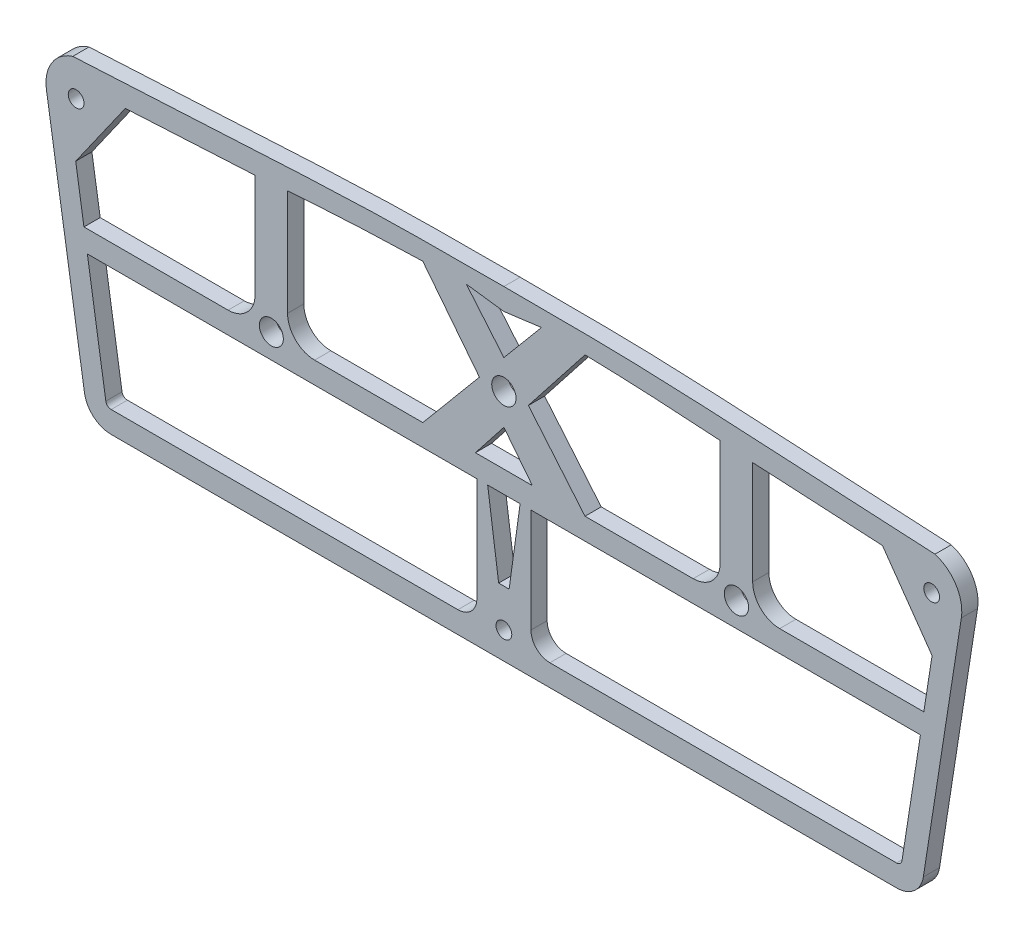
SolidWorks part; units mm, degrees
ref_plane "Alzado" through (0, 0, 0) normal (0, 0, 1) x (1, 0, 0)
ref_plane "Planta" through (0, 0, 0) normal (0, 1, 0) x (1, 0, 0)
ref_plane "Vista lateral" through (0, 0, 0) normal (1, 0, 0) x (0, 0, -1)
sketch "Croquis1" plane through (0, 0, 0) normal (0, 0, 1) x (1, 0, 0)
  line L0 (72.621, -42.7139) -> (-72.621, -42.7139)
  line L1 (79.7182, 14.2861) -> (-79.7182, 14.2861) construction
  line L2 (0, 14.2861) -> (0, 17.2861) construction
  line L3 (-77.7935, 17.2861) -> (77.7935, 17.2861) construction
  line L4 (0, -40.4126) -> (0, 34.1548) construction
  line L5 (-25, 41.2162) -> (-25, -46.3712) construction
  line L6 (-77.5611, -38.4855) -> (-84.5891, 6.5113)
  line L11 (25, 41.2162) -> (25, -46.3712) construction
  line L14 (77.5611, -38.4855) -> (84.5891, 6.5113)
  arc A0 (84.5891, 6.5113) -> (79.7182, 14.2861) centre (77.6729, 7.5915) ccw
  arc A1 (77.5611, -38.4855) -> (72.621, -42.7139) centre (72.621, -37.7139) cw
  arc A2 (-77.5611, -38.4855) -> (-72.621, -42.7139) centre (-72.621, -37.7139) ccw
  arc A3 (-84.5891, 6.5113) -> (-79.7182, 14.2861) centre (-77.6729, 7.5915) cw
  conic Q0 (79.7182, 14.2861) -> (0, 17.2861) control (25, 17.2861) rho 0.75
  conic Q1 (-79.7182, 14.2861) -> (0, 17.2861) control (-25, 17.2861) rho 0.75
  point P15 (-84.627, 12.5288)
  point P27 (0, -42.7139)
  point P28 (0, -42.7139)
  point P40 (0, 9.5288)
  point P61 (0, -42.7139)
  point P62 (84.627, 12.5288)
  dimension "D1" = 5
  dimension "D2" = 7
  dimension "D4" = 60
  dimension "D3" = 3
extrude "Saliente-Extruir3" add sketch "Croquis1" along normal blind 3 contours Q0 Q1 A3 L6 A2 L0 A1 L14 A0
sketch "Croquis10" plane through (0, 0, 0) normal (0, 0, -1) x (-1, 0, 0)
  line L0 (-79.1761, -2.225) -> (-70, 10.8116)
  line L1 (79.1761, -2.225) -> (70, 10.8116)
  line L2 (46, -6.9974) -> (46, 12.0975)
  line L3 (-89.1533, -2.1273) -> (0, -3.0001) construction
  line L4 (-70, 32.4884) -> (-70, -57.6963) construction
  line L5 (70, -55.635) -> (70, -62.635) construction
  line L6 (-80.637, 7.1286) -> (-73.609, -37.8682)
  line L7 (-72.621, -38.7139) -> (72.621, -38.7139)
  line L8 (73.609, -37.8682) -> (80.637, 7.1286)
  line L9 (-79.1761, -2.225) -> (-77.6497, -11.9974)
  line L10 (-72.621, -38.7139) -> (-8.5, -38.7139)
  line L11 (73.609, -37.8682) -> (77.025, -15.9974)
  line L12 (0, -66.0706) -> (0, -38.7139) construction
  line L13 (-5, -34.7139) -> (-5, -35.2139)
  line L14 (5, -34.7139) -> (5, -35.2139)
  line L15 (-72.621, -42.7139) -> (72.621, -42.7139) construction
  line L16 (8.5, -38.7139) -> (72.621, -38.7139)
  line L17 (0, -30.688) -> (0, -3.0001) construction
  line L18 (2.4598, -37.7139) -> (-1.8908, -37.7139) construction
  line L19 (77.5724, -13.7139) -> (-84.3115, -13.7139) construction
  line L20 (77.025, -15.9974) -> (15, -15.9974)
  line L21 (35, -11.9974) -> (15, -11.9974)
  line L22 (15, 26.347) -> (15, -53.1774) construction
  line L24 (-15, -38.7139) -> (-15, -55.635) construction
  line L26 (-0.9683, -30.688) -> (-3, -15.9974)
  line L27 (0.9683, -30.688) -> (3, -15.9974)
  line L28 (-0.9683, -30.688) -> (0, -30.688)
  line L29 (3, -15.9974) -> (0, -15.9974)
  line L30 (-15, -15.9974) -> (-77.025, -15.9974)
  line L31 (79.1761, -2.225) -> (77.6497, -11.9974)
  line L32 (-77.025, -15.9974) -> (-73.609, -37.8682)
  line L33 (40, -6.9974) -> (40, 12.6316)
  line L34 (5.2644, -11.9561) -> (-5.2644, -11.9561)
  line L35 (-46, 12.0975) -> (-46, -6.9974)
  line L36 (51, -11.9974) -> (77.6497, -11.9974)
  line L37 (-51, -11.9974) -> (-77.6497, -11.9974)
  line L38 (-40, 12.6316) -> (-40, -6.9974)
  line L39 (-15, -11.9974) -> (-4.5237, 0.5057)
  line L40 (15, -11.9974) -> (4.5237, 0.5057)
  line L42 (-15, -11.9974) -> (-35, -11.9974)
  line L44 (46, -6.9974) -> (40, -6.9974) construction
  line L45 (43, -6.9974) -> (43, -15.9974) construction
  line L46 (-40, -3.91) -> (-46, -3.91) construction
  line L47 (-46, -3.91) -> (-43, -3.91) construction
  line L48 (-43, -3.91) -> (-43, -19.0848) construction
  line L49 (0, -30.688) -> (0.9683, -30.688)
  line L50 (0, -15.9974) -> (-3, -15.9974)
  line L51 (-5.2644, -11.9561) -> (0, -5.2536)
  line L52 (-15, 13.8437) -> (-4.5237, 0.5057)
  line L53 (0, 5.9046) -> (-6.9466, 14.1951)
  line L54 (0, 5.9046) -> (6.9466, 14.1951)
  line L55 (0, 5.9046) -> (0, 45.5866) construction
  line L56 (1.7565, -3.0173) -> (92.9339, -3.91) construction
  line L57 (4.5237, 0.5057) -> (15, 13.8437)
  line L58 (0, -5.2536) -> (5.2644, -11.9561)
  line L59 (4.5237, 0.5057) -> (-4.5237, 0.5057) construction
  line L60 (43, -11.4974) -> (-56.9157, -11.4974) construction
  line L61 (15, -15.9974) -> (5, -15.9974)
  line L62 (5, -15.9974) -> (5, -34.7139)
  line L63 (-5, -34.7139) -> (-5, -15.9974)
  line L64 (-5, -15.9974) -> (-15, -15.9974)
  arc A0 (-5, -35.2139) -> (-8.5, -38.7139) centre (-8.5, -35.2139) cw
  arc A1 (8.5, -38.7139) -> (5, -35.2139) centre (8.5, -35.2139) cw
  arc A2 (40, -6.9974) -> (35, -11.9974) centre (35, -6.9974) cw
  arc A3 (46, -6.9974) -> (51, -11.9974) centre (51, -6.9974) ccw
  arc A4 (-51, -11.9974) -> (-46, -6.9974) centre (-51, -6.9974) ccw
  arc A5 (-35, -11.9974) -> (-40, -6.9974) centre (-35, -6.9974) cw
  circle A6 centre (43, -11.4974) radius 2.2165
  circle A7 centre (-43, -11.4974) radius 2.25
  arc A8 (-78.9106, 10.3243) -> (-80.637, 7.1286) centre (-77.6729, 7.5915) ccw
  arc A9 (-73.609, -37.8682) -> (-72.621, -38.7139) centre (-72.621, -37.7139) ccw
  arc A10 (72.621, -38.7139) -> (73.609, -37.8682) centre (72.621, -37.7139) ccw
  arc A11 (80.637, 7.1286) -> (78.9106, 10.3243) centre (77.6729, 7.5915) ccw
  circle A12 centre (0, 0.5057) radius 2.25
  arc A13 (-73.609, -37.8682) -> (-72.621, -38.7139) centre (-72.621, -37.7139) ccw
  arc A14 (72.621, -38.7139) -> (73.609, -37.8682) centre (72.621, -37.7139) ccw
  spline S0 degree 3 poles (-46, 12.0975) (-50.3985, 11.8702) (-54.7965, 11.6342) (-62.7964, 11.2034) (-66.3982, 11.008) (-70, 10.8116) knots 0.582707 0.582707 0.582707 0.582707 0.75 0.75 0.887012 0.887012 0.887012 0.887012
  spline S1 degree 3 poles (40, 12.6316) (39.8254, 12.6429) (39.6508, 12.6542) (36.1907, 12.8778) (32.9047, 13.0827) (26.3302, 13.4427) (23.0414, 13.5928) (18.1671, 13.7577) (16.5836, 13.8034) (15, 13.8437) knots 0.493358 0.493358 0.493358 0.493358 0.5 0.5 0.625 0.625 0.75 0.75 0.810141 0.810141 0.810141 0.810141
  spline S2 degree 3 poles (6.9466, 14.1951) (4.6306, 13.8958) (2.3152, 13.5918) (0, 13.2861) knots 0.911343 0.911343 0.911343 0.911343 1 1 1 1
  spline S3 degree 3 poles (-15, 13.8437) (-16.5836, 13.8034) (-18.1671, 13.7577) (-23.0414, 13.5928) (-26.3302, 13.4427) (-32.9047, 13.0827) (-36.1907, 12.8778) (-39.6508, 12.6542) (-39.8254, 12.6429) (-40, 12.6316) knots 0.189858 0.189858 0.189858 0.189858 0.25 0.25 0.375 0.375 0.5 0.5 0.506642 0.506642 0.506642 0.506642
  spline S4 degree 3 poles (1023.8412, 337.5933) (688.2712, -34.0559) (374.0407, -5.5562) (52.6222, 11.7513) (46.0499, 12.1034) (36.1891, 12.5892) (32.9019, 12.7438) (26.3256, 13.0031) (23.0364, 13.1028) (16.455, 13.2247) (13.1641, 13.2517) (-151.4659, 14.0208) (-312.9806, -13.553) (-468.678, 896.6381) knots -11.726351 -11.726351 -11.726351 -11.726351 0.25 0.25 0.5 0.5 0.625 0.625 0.75 0.75 0.875 0.875 7.003082 7.003082 7.003082 7.003082 only from (78.9106, 10.3243) to (0, 13.2861)
  spline S5 degree 3 poles (468.6965, 896.6433) (312.9806, -13.5531) (151.4662, 14.0208) (-13.1641, 13.2517) (-16.455, 13.2247) (-23.0364, 13.1028) (-26.3256, 13.0031) (-32.9019, 12.7438) (-36.1891, 12.5892) (-46.0499, 12.1034) (-52.6222, 11.7513) (-374.041, -5.5562) (-688.2719, -34.056) (-1023.8404, 337.5944) knots -6.00309 -6.00309 -6.00309 -6.00309 0.125 0.125 0.25 0.25 0.375 0.375 0.5 0.5 0.75 0.75 12.726363 12.726363 12.726363 12.726363 only from (0, 13.2861) to (-78.9106, 10.3243)
  spline S6 degree 3 poles (70, 10.8116) (66.3982, 11.008) (62.7964, 11.2034) (54.7965, 11.6342) (50.3985, 11.8702) (46, 12.0975) knots 0.112988 0.112988 0.112988 0.112988 0.25 0.25 0.417293 0.417293 0.417293 0.417293
  spline S7 degree 3 poles (0, 13.2861) (-2.3152, 13.5918) (-4.6306, 13.8958) (-6.9466, 14.1951) knots 0 0 0 0 0.088657 0.088657 0.088657 0.088657
  point P8 (-79.1761, -2.225)
  point P9 (-70, 10.8116)
  point P43 (0, -37.7139)
  point P54 (-15, -15.9974)
  point P55 (15, -15.9974)
  point P74 (46, -11.9974)
  dimension "D17" = 5
  dimension "D18" = 5
  dimension "D21" = 3
  dimension "D2" = 70
  dimension "D3" = 70
  dimension "D4" = 3
  dimension "D5" = 10
  dimension "D9" = 5
  dimension "D10" = 25
  dimension "D11" = 4
  dimension "D13" = 15
  dimension "D14" = 40
  dimension "D15" = 6
  dimension "D22" = 3
  dimension "D1" = 4
extrude "Cortar-Extruir2" cut sketch "Croquis10" against normal blind 3
sketch "Croquis11" plane through (0, 0, 0) normal (0, 0, -1) x (-1, 0, 0)
  line L0 (-74.588, 4.2933) -> (-83.6049, 11.3079) construction
  line L1 (-70, 10.8116) -> (-79.1761, -2.225) construction
  line L2 (74.588, 4.2933) -> (83.6049, 11.3079) construction
  line L3 (79.1761, -2.225) -> (70, 10.8116) construction
  line L4 (0, 0) -> (0, -72.0529) construction
  line L5 (4.267, -37.7139) -> (-4.5681, -37.7139) construction
  line L6 (-72.621, -42.7139) -> (72.621, -42.7139) construction
  arc A0 (-79.7182, 14.2861) -> (-84.5891, 6.5113) centre (-77.6729, 7.5915) ccw construction
  arc A1 (84.5891, 6.5113) -> (79.7182, 14.2861) centre (77.6729, 7.5915) ccw construction
  point P14 (79.0965, 7.8006)
  point P15 (-79.0965, 7.8006)
  point P23 (0, -37.7139)
  dimension "D1" = 5
hole_wizard "Taladro de margen para #32" positions "Croquis3D1" profile "Croquis12" hole size "#3" standard "Ansi Inch" end condition through all
sketch3d "Croquis3D1"
  point P0 (79.0965, 7.8006, 0)
  point P3 (-79.0965, 7.8006, 0)
sketch "Croquis12" plane through (79.0965, 7.8006, 0) normal (1, 0, 0) x (0, 1, 0)
  line L0 (0, 0) -> (0, 3.01)
  line L1 (0, 3.01) -> (1.4605, 3.01)
  line L2 (1.4605, 3.01) -> (1.4605, 0)
  line L5 (1.4605, 0) -> (0, 0)
  line L11 (0, -6.35) -> (0, 107.95) construction
  dimension "Diámetro de taladro hasta el siguiente" = 2.921
  dimension "Profundidad de taladro hasta el siguiente" = 3.01
hole_wizard "Taladro de margen para #33" positions "Croquis3D6" profile "Croquis17" hole size "#3" standard "Ansi Inch" end condition through all
sketch3d "Croquis3D6"
  point P0 (0, -37.7139, 0)
sketch "Croquis17" plane through (0, -37.7139, 0) normal (1, 0, 0) x (0, 1, 0)
  line L0 (0, 0) -> (0, 3.01)
  line L1 (0, 3.01) -> (1.4605, 3.01)
  line L2 (1.4605, 3.01) -> (1.4605, 0)
  line L5 (1.4605, 0) -> (0, 0)
  line L11 (0, -6.35) -> (0, 107.95) construction
  dimension "Diámetro de taladro hasta el siguiente" = 2.921
  dimension "Profundidad de taladro hasta el siguiente" = 3.01
